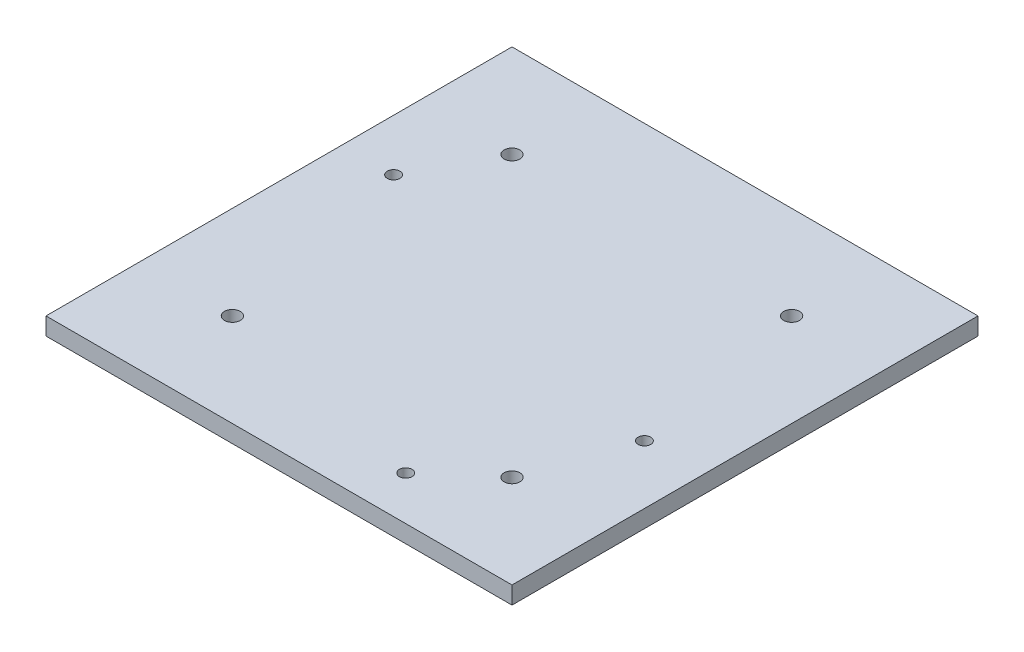
SolidWorks part; units mm, degrees
ref_plane "Front Plane" through (0, 0, 0) normal (0, 0, 1) x (1, 0, 0)
ref_plane "Top Plane" through (0, 0, 0) normal (0, 1, 0) x (1, 0, 0)
ref_plane "Right Plane" through (0, 0, 0) normal (1, 0, 0) x (0, 0, -1)
sketch "Sketch1" plane through (0, 0, 0) normal (0, 1, 0) x (1, 0, 0)
  line L1 (-106.3365, 80.1768) -> (20.6635, 80.1768)
  line L2 (-106.3365, 80.1768) -> (-106.3365, -46.8232)
  line L3 (-106.3365, -46.8232) -> (20.6635, -46.8232)
  line L4 (20.6635, 80.1768) -> (20.6635, -46.8232)
  line L5 (-106.3365, 80.1768) -> (20.6635, -46.8232) construction
  line L6 (-106.3365, -46.8232) -> (20.6635, 80.1768) construction
  point P0 (-42.8365, 16.6768)
  dimension "D1" = 127
  dimension "D2" = 127
extrude "Boss-Extrude1" add sketch "Sketch1" along normal blind 4.7625
sketch "Sketch3" plane through (0, 4.7625, 0) normal (0, 1, 0) x (1, 0, 0)
  circle A0 centre (-92.2813, 33.85) radius 1.7272
  circle A1 centre (4.6808, 5.2504) radius 1.7272
  circle A2 centre (-20.2437, -34.8839) radius 1.7272
  dimension "D1" = 3.4544
extrude "Cut-Extrude2" cut sketch "Sketch3" against normal through all
hole_wizard "#18 (0.1695) Diameter Hole1" positions "Sketch4" profile "Sketch5" hole size "#18" standard "ANSI Inch" end condition through all
sketch "Sketch4" plane through (0, 0, 0) normal (0, -1, 0) x (-1, 0, 0)
  line L0 (-20.6635, 80.1768) -> (106.3365, -46.8232) construction
  line L3 (4.7365, -21.4232) -> (80.9365, -21.4232) construction
  line L4 (4.7365, -21.4232) -> (4.7365, 54.7768) construction
  line L5 (4.7365, 54.7768) -> (80.9365, 54.7768) construction
  line L6 (80.9365, -21.4232) -> (80.9365, 54.7768) construction
  line L7 (4.7365, -21.4232) -> (80.9365, 54.7768) construction
  line L8 (4.7365, 54.7768) -> (80.9365, -21.4232) construction
  line L9 (-20.6635, -46.8232) -> (-20.6635, 80.1768) construction
  line L10 (106.3365, -46.8232) -> (-20.6635, -46.8232) construction
  point P7 (80.9365, 54.7768)
  point P30 (4.7365, -21.4232)
  point P31 (4.7365, 54.7768)
  point P32 (80.9365, -21.4232)
  dimension "D1" = 76.2
  dimension "D2" = 76.2
  dimension "D3" = 25.4
  dimension "D4" = 25.4
sketch "Sketch5" plane through (-80.9365, 0, 21.4232) normal (1, 0, 0) x (0, 0, -1)
  line L0 (0, 0) -> (0, 4.7625)
  line L1 (0, 4.7625) -> (2.1526, 4.7625)
  line L2 (2.1526, 4.7625) -> (2.1526, 0)
  line L5 (2.1526, 0) -> (0, 0)
  line L11 (0, -6.35) -> (0, 107.95) construction
  dimension "Thru Hole Dia." = 4.3053
  dimension "Thru Hole Depth" = 4.7625
